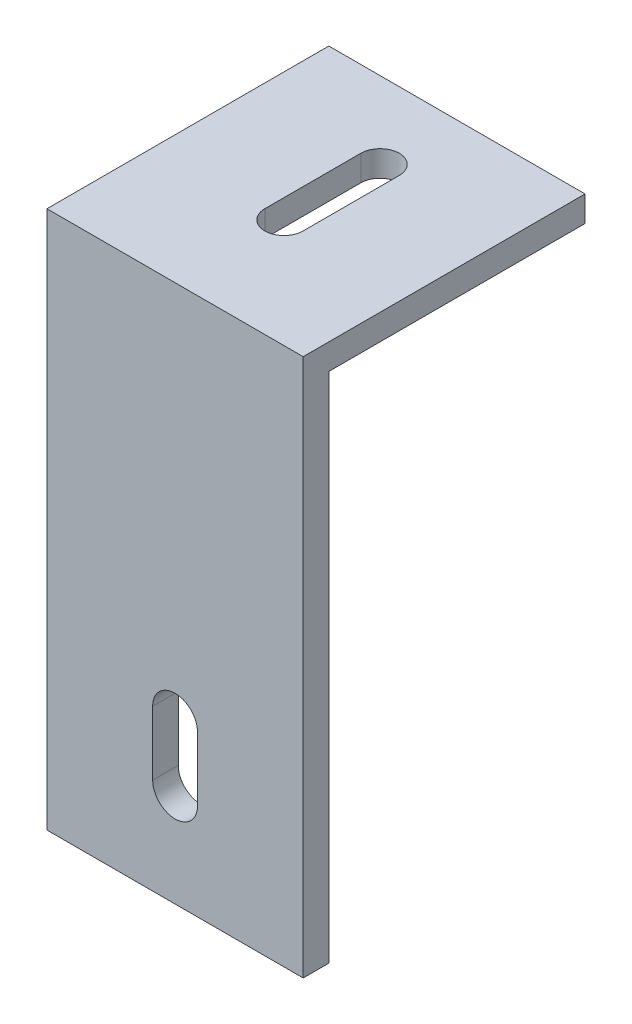
SolidWorks part; units mm, degrees
ref_plane "前视基准面" through (0, 0, 0) normal (0, 0, 1) x (1, 0, 0)
ref_plane "上视基准面" through (0, 0, 0) normal (0, 1, 0) x (1, 0, 0)
ref_plane "右视基准面" through (0, 0, 0) normal (1, 0, 0) x (0, 0, -1)
sketch "草图1" plane through (0, 0, 0) normal (1, 0, 0) x (0, 0, -1)
  line L0 (0, 0) -> (0, 84)
  line L1 (0, 84) -> (44, 84)
  line L2 (44, 84) -> (44, 80)
  line L3 (44, 80) -> (4, 80)
  line L4 (4, 80) -> (4, 0)
  line L5 (4, 0) -> (0, 0)
  dimension "D1" = 4
  dimension "D2" = 4
  dimension "D3" = 80
  dimension "D4" = 40
extrude "凸台-拉伸1" add sketch "草图1" along normal blind 40
sketch "草图2" plane through (0, 84, 0) normal (0, 1, 0) x (1, 0, 0)
  line L0 (17, 32) -> (17, 17)
  line L1 (23, 17) -> (23, 32)
  line L2 (40, 44) -> (0, 44) construction
  arc A0 (23, 32) -> (17, 32) centre (20, 32) ccw
  arc A1 (17, 17) -> (23, 17) centre (20, 17) ccw
  dimension "D2" = 6
  dimension "D3" = 6
  dimension "D4" = 12
  dimension "D1" = 15
extrude "切除-拉伸1" cut sketch "草图2" against normal up to next
sketch "草图3" plane through (0, 0, 0) normal (0, 0, 1) x (1, 0, 0)
  line L0 (23.5, 15) -> (23.5, 25)
  line L1 (16.5, 25) -> (16.5, 15)
  line L2 (40, 0) -> (0, 0) construction
  line L3 (0, 84) -> (0, 0) construction
  arc A0 (16.5, 15) -> (23.5, 15) centre (20, 15) ccw
  arc A1 (23.5, 25) -> (16.5, 25) centre (20, 25) ccw
  point P8 (20, 0)
  dimension "D2" = 15
  dimension "D3" = 3.5
  dimension "D4" = 20
  dimension "D1" = 10
extrude "切除-拉伸2" cut sketch "草图3" against normal up to next
sketch "草图4" plane through (0, 0, 0) normal (1, 0, 0) x (0, 0, -1)
